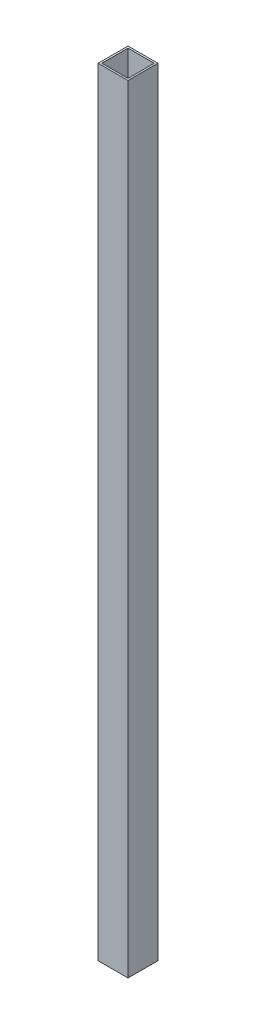
SolidWorks part; units mm, degrees
ref_plane "Front Plane" through (0, 0, 0) normal (0, 0, 1) x (1, 0, 0)
ref_plane "Top Plane" through (0, 0, 0) normal (0, 1, 0) x (1, 0, 0)
ref_plane "Right Plane" through (0, 0, 0) normal (1, 0, 0) x (0, 0, -1)
sketch "Sketch1" plane through (0, 0, 0) normal (0, 1, 0) x (1, 0, 0)
  line L1 (12.7, -12.7) -> (-12.7, -12.7)
  line L2 (12.7, -12.7) -> (12.7, 12.7)
  line L3 (12.7, 12.7) -> (-12.7, 12.7)
  line L4 (-12.7, -12.7) -> (-12.7, 12.7)
  line L5 (12.7, -12.7) -> (-12.7, 12.7) construction
  line L6 (12.7, 12.7) -> (-12.7, -12.7) construction
  line L7 (11.1125, -11.1125) -> (-11.1125, -11.1125)
  line L8 (11.1125, -11.1125) -> (11.1125, 11.1125)
  line L9 (11.1125, 11.1125) -> (-11.1125, 11.1125)
  line L10 (-11.1125, -11.1125) -> (-11.1125, 11.1125)
  line L11 (11.1125, -11.1125) -> (-11.1125, 11.1125) construction
  line L12 (11.1125, 11.1125) -> (-11.1125, -11.1125) construction
  point P0 (0, 0)
  point P6 (0, 0)
  dimension "D1" = 25.4
  dimension "D2" = 25.4
  dimension "D3" = 1.5875
extrude "Boss-Extrude1" add sketch "Sketch1" along normal blind 660.4
